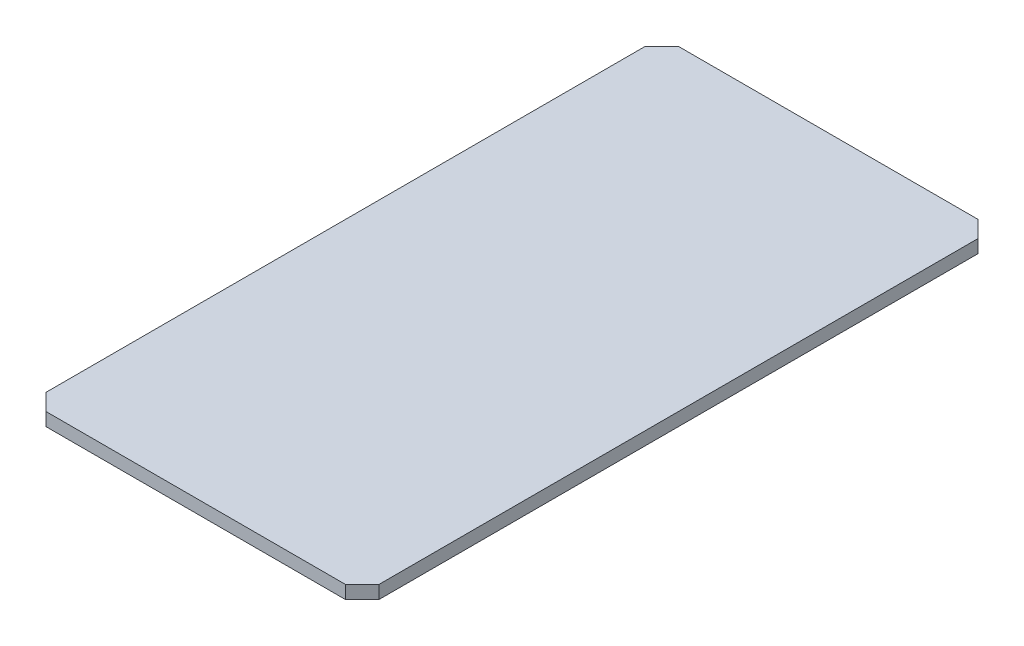
SolidWorks part; units mm, degrees
ref_plane "Front Plane" through (0, 0, 0) normal (0, 0, 1) x (1, 0, 0)
ref_plane "Top Plane" through (0, 0, 0) normal (0, 1, 0) x (1, 0, 0)
ref_plane "Right Plane" through (0, 0, 0) normal (1, 0, 0) x (0, 0, -1)
sketch "Sketch1" plane through (0, 0, 0) normal (0, 1, 0) x (1, 0, 0)
  line L0 (-31.41, 35.5845) -> (-30.14, 36.8545)
  line L1 (-30.14, 36.8545) -> (-7.28, 36.8545)
  line L2 (-31.41, 35.5845) -> (-31.41, -10.1355)
  line L3 (-30.14, -11.4055) -> (-7.28, -11.4055)
  line L4 (-6.01, 35.5845) -> (-6.01, -10.1355)
  line L5 (-7.28, 36.8545) -> (-6.01, 35.5845)
  line L6 (-6.01, -10.1355) -> (-7.28, -11.4055)
  line L7 (-31.41, -10.1355) -> (-30.14, -11.4055)
  point P0 (-31.41, 36.8545)
  point P1 (-6.01, -11.4055)
  point P2 (-31.41, -11.4055)
  point P3 (-6.01, 36.8545)
  dimension "D1" = 1.27
  dimension "D2" = 1.27
  dimension "D3" = 1.27
  dimension "D4" = 1.27
  dimension "D5" = 1.27
  dimension "D6" = 1.27
  dimension "D7" = 1.27
  dimension "D8" = 1.27
extrude "Boss-Extrude1" add sketch "Sketch1" along normal blind 1
sketch "Sketch3" plane through (0, 1, 0) normal (0, 1, 0) x (1, 0, 0)
  circle A0 centre (-30.14, 35.5845) radius 0.75
  circle A1 centre (-30.14, -10.1355) radius 0.75
  circle A2 centre (-7.28, -10.1355) radius 0.75
  circle A3 centre (-7.28, 35.5845) radius 0.75
  point P3 (0, 0)
